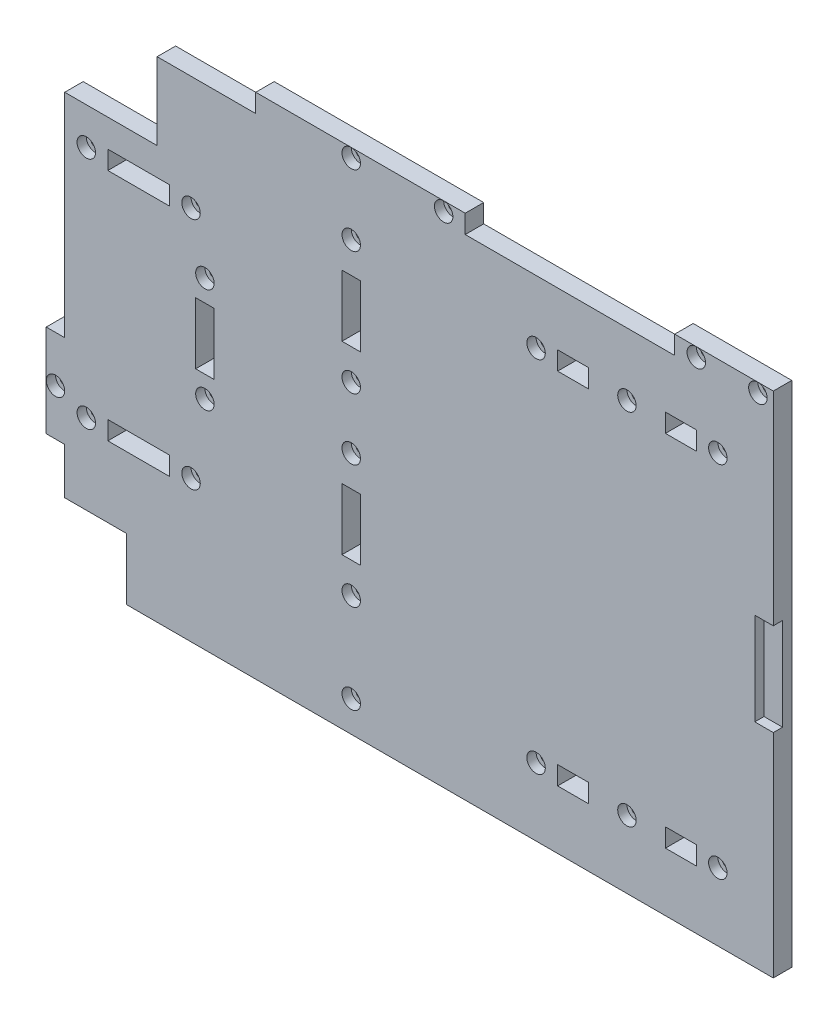
SolidWorks part; units mm, degrees
ref_plane "Plan de face" through (0, 0, 0) normal (0, 0, 1) x (1, 0, 0)
ref_plane "Plan de dessus" through (0, 0, 0) normal (0, 1, 0) x (1, 0, 0)
ref_plane "Plan de droite" through (0, 0, 0) normal (1, 0, 0) x (0, 0, -1)
sketch "Esquisse1" plane through (0, 0, 0) normal (0, 0, 1) x (1, 0, 0)
  line L1 (0, 0) -> (-340, 0)
  line L2 (0, 0) -> (0, 148)
  line L3 (0, 148) -> (-340, 148)
  line L4 (-340, 0) -> (-340, 148)
  dimension "D1" = 148
  dimension "D2" = 340
extrude "Boss.-Extru.1" add sketch "Esquisse1" along normal blind 6
sketch "Esquisse2" plane through (0, 0, 6) normal (0, 0, 1) x (1, 0, 0)
  line L0 (0, 0) -> (0, 148) construction
  line L1 (0, 148) -> (-340, 148) construction
  line L2 (-272, 142) -> (-334, 142)
  line L3 (-340, 148) -> (-340, 48)
  line L4 (0, 148) -> (0, 118)
  line L5 (0, 0) -> (-6, 0)
  line L6 (-340, 148) -> (-272, 148)
  line L7 (0, 0) -> (0, 28)
  line L8 (-340, 48) -> (-334, 48)
  line L9 (-334, 142) -> (-334, 48)
  line L11 (-340, 0) -> (-334, 0)
  line L12 (-340, 0) -> (-340, 18)
  line L13 (0, 28) -> (-6, 28)
  line L14 (-272, 148) -> (-272, 142)
  line L15 (-204, 148) -> (-136, 148)
  line L16 (-204, 148) -> (-204, 142)
  line L17 (-204, 142) -> (-136, 142)
  line L18 (-6, 0) -> (-6, 28)
  line L19 (0, 58) -> (-6, 58)
  line L20 (0, 58) -> (0, 88)
  line L21 (0, 88) -> (-6, 88)
  line L22 (-136, 148) -> (-136, 142)
  line L23 (0, 148) -> (-68, 148)
  line L24 (-340, 18) -> (-334, 18)
  line L25 (-6, 142) -> (-68, 142)
  line L26 (-68, 148) -> (-68, 142)
  line L27 (-334, 0) -> (-334, 18)
  line L29 (-6, 58) -> (-6, 88)
  line L32 (0, 118) -> (-6, 118)
  line L33 (-6, 142) -> (-6, 118)
  dimension "D3" = 68
  dimension "D4" = 6
  dimension "D5" = 100
  dimension "D6" = 68
  dimension "D7" = 30
  dimension "D8" = 6
  dimension "D9" = 30
  dimension "D10" = 30
  dimension "D11" = 24
  dimension "D12" = 30
  dimension "D13" = 6
  dimension "D14" = 68
  dimension "D15" = 6
  dimension "D16" = 6
  dimension "D18" = 6
  dimension "D20" = 6
  dimension "D21" = 6
extrude "Enlèv. mat.-Extru.1" cut sketch "Esquisse2" against normal blind 6
sketch "Esquisse3" plane through (0, 0, 6) normal (0, 0, 1) x (1, 0, 0)
  line L0 (-204, 148) -> (-272, 148) construction
  line L1 (-238, 32) -> (-244, 32)
  line L2 (-340, 48) -> (-340, 18) construction
  line L3 (-238, 112) -> (-244, 112)
  line L4 (-238, 112) -> (-238, 92)
  line L5 (-238, 92) -> (-244, 92)
  line L6 (-340, 48) -> (-340, 18) construction
  line L7 (-238, 52) -> (-244, 52)
  line L8 (-238, 52) -> (-238, 32)
  line L9 (-244, 112) -> (-244, 92)
  line L10 (-244, 52) -> (-244, 32)
  line L11 (-285.5, 80.5) -> (-291.5, 80.5)
  line L12 (-334, 0) -> (-6, 0) construction
  line L13 (-285.5, 80.5) -> (-285.5, 60.5)
  line L14 (-285.5, 60.5) -> (-291.5, 60.5)
  line L15 (-291.5, 80.5) -> (-291.5, 60.5)
  line L16 (-68, 142) -> (-6, 142) construction
  line L17 (-334, 142) -> (-304, 142)
  line L18 (-334, 142) -> (-334, 117)
  line L19 (-334, 117) -> (-304, 117)
  line L20 (-304, 142) -> (-304, 117)
  line L21 (-300, 108) -> (-320, 108)
  line L22 (-300, 108) -> (-300, 102)
  line L23 (-300, 102) -> (-320, 102)
  line L24 (-320, 108) -> (-320, 102)
  line L25 (-300, 32) -> (-320, 32)
  line L26 (-300, 32) -> (-300, 26)
  line L27 (-300, 26) -> (-320, 26)
  line L28 (-320, 32) -> (-320, 26)
  line L29 (-64, 112) -> (-70, 112)
  line L30 (-64, 112) -> (-64, 92)
  line L31 (-64, 92) -> (-70, 92)
  line L32 (-70, 112) -> (-70, 92)
  line L33 (0, 88) -> (0, 118) construction
  dimension "D1" = 20
  dimension "D2" = 20
  dimension "D3" = 40
  dimension "D4" = 96
  dimension "D5" = 96
  dimension "D6" = 6
  dimension "D7" = 6
  dimension "D8" = 92
  dimension "D9" = 6
  dimension "D10" = 20
  dimension "D11" = 48.5
  dimension "D12" = 67.5
  dimension "D13" = 30
  dimension "D14" = 25
  dimension "D15" = 20
  dimension "D16" = 6
  dimension "D17" = 40
  dimension "D18" = 20
  dimension "D19" = 20
  dimension "D20" = 6
  dimension "D21" = 70
  dimension "D22" = 20
  dimension "D23" = 20
  dimension "D24" = 30
  dimension "D25" = 6
  dimension "D26" = 70
extrude "Enlèv. mat.-Extru.2" cut sketch "Esquisse3" against normal blind 10
sketch "Esquisse4" plane through (0, 0, 6) normal (0, 0, 1) x (1, 0, 0)
  line L0 (-334, 48) -> (-334, 117) construction
  line L1 (-164, 124.6) -> (-174, 124.6)
  line L2 (-164, 124.6) -> (-164, 118.6)
  line L3 (-164, 118.6) -> (-174, 118.6)
  line L4 (-174, 124.6) -> (-174, 118.6)
  line L5 (-204, 148) -> (-272, 148) construction
  line L6 (-68, 148) -> (-136, 148) construction
  line L7 (-139, 124.6) -> (-129, 124.6)
  line L8 (-139, 124.6) -> (-139, 118.6)
  line L9 (-139, 118.6) -> (-129, 118.6)
  line L10 (-129, 124.6) -> (-129, 118.6)
  line L12 (-129, 8) -> (-139, 8)
  line L13 (-129, 8) -> (-129, 2)
  line L14 (-129, 2) -> (-139, 2)
  line L15 (-139, 8) -> (-139, 2)
  line L16 (-68, 148) -> (-136, 148) construction
  line L17 (-164, 8) -> (-174, 8)
  line L18 (-164, 8) -> (-164, 2)
  line L19 (-164, 2) -> (-174, 2)
  line L20 (-174, 8) -> (-174, 2)
  line L21 (-204, 148) -> (-272, 148) construction
  line L22 (-204, 142) -> (-136, 142) construction
  line L23 (-340, 48) -> (-340, 18) construction
  circle A0 centre (-151.5, 121.6) radius 1.5
  circle A1 centre (-151.5, 5) radius 1.5
  dimension "D7" = 3
  dimension "D14" = 140
  dimension "D16" = 137
  dimension "D19" = 3
  dimension "D1" = 10
  dimension "D2" = 6
  dimension "D3" = 160
  dimension "D4" = 23.4
  dimension "D5" = 10
  dimension "D6" = 25
  dimension "D8" = 12.5
  dimension "D9" = 23.4
  dimension "D10" = 26.4
  dimension "D11" = 6
  dimension "D12" = 6
  dimension "D13" = 6
  dimension "D15" = 140
  dimension "D17" = 12.5
  dimension "D18" = 25
  dimension "D20" = 166
  dimension "D21" = 10
  dimension "D22" = 10
extrude "Enlèv. mat.-Extru.3" cut sketch "Esquisse4" against normal blind 10
sketch "Esquisse7" plane through (0, 0, 0) normal (0, -1, 0) x (1, 0, 0)
  line L0 (-334, 6) -> (-6, 6) construction
  line L1 (-334, 6) -> (-6, 6)
  line L2 (-334, 6) -> (-334, 0)
  line L3 (-334, 0) -> (-6, 0)
  line L4 (-6, 6) -> (-6, 0)
  line L5 (-340, 6) -> (-340, 0) construction
  dimension "D1" = 6
extrude "Boss.-Extru.2" add sketch "Esquisse7" along normal blind 17
sketch "Esquisse8" plane through (0, 0, 6) normal (0, 0, 1) x (1, 0, 0)
  line L0 (-241, 115.6483) -> (-241, 35.6483) construction
  line L1 (-334, -17) -> (-314, -17)
  line L2 (-334, -17) -> (-334, 3)
  line L3 (-334, 3) -> (-314, 3)
  line L4 (-314, -17) -> (-314, 3)
  line L5 (-174, 124.6) -> (-174, 118.6) construction
  line L6 (-164, 124.6) -> (-174, 124.6) construction
  line L7 (-300, 102) -> (-300, 108) construction
  line L8 (-300, 108) -> (-320, 108) construction
  line L9 (-285.5, 80.5) -> (-291.5, 80.5) construction
  line L10 (-285.5, 60.5) -> (-285.5, 80.5) construction
  line L11 (-291.5, 60.5) -> (-285.5, 60.5) construction
  line L12 (-291.5, 80.5) -> (-291.5, 60.5) construction
  line L13 (-320, 108) -> (-320, 102) construction
  line L14 (-300, 26) -> (-300, 32) construction
  line L15 (-300, 32) -> (-320, 32) construction
  line L16 (-320, 32) -> (-320, 26) construction
  line L17 (-340, 48) -> (-340, 18) construction
  line L18 (-334, 18) -> (-340, 18) construction
  line L19 (-204, 148) -> (-272, 148) construction
  line L20 (-238, 112) -> (-244, 112) construction
  line L21 (-244, 92) -> (-238, 92) construction
  line L22 (-238, 52) -> (-244, 52) construction
  line L23 (-244, 32) -> (-238, 32) construction
  line L24 (-6, -17) -> (-334, -17) construction
  line L25 (-334, 48) -> (-334, 117) construction
  line L26 (-204, 148) -> (-204, 142) construction
  line L27 (-68, 148) -> (-136, 148) construction
  line L28 (-136, 142) -> (-136, 148) construction
  line L29 (-68, 148) -> (-68, 142) construction
  line L30 (-129, 118.6) -> (-129, 124.6) construction
  line L31 (-139, 118.6) -> (-129, 118.6) construction
  line L32 (-174, 8) -> (-174, 2) construction
  line L33 (-174, 2) -> (-164, 2) construction
  line L34 (-129, 2) -> (-129, 8) construction
  line L36 (-129, 8) -> (-139, 8) construction
  line L37 (0, 88) -> (-6, 88) construction
  line L39 (-6, 88) -> (-6, 58) construction
  line L40 (0, 88) -> (0, 118) construction
  line L41 (-6, 118) -> (0, 118) construction
  line L42 (0, 28) -> (0, 58) construction
  line L43 (-6, 58) -> (0, 58) construction
  line L45 (0, 28) -> (-6, 28) construction
  circle A0 centre (-75, 145) radius 1.5
  circle A1 centre (-129, 145) radius 1.5
  circle A2 centre (-109, 145) radius 1.5
  circle A3 centre (-3, 111) radius 1.5
  circle A4 centre (-3, 95) radius 1.5
  circle A5 centre (-3, 51) radius 1.5
  circle A6 centre (-3, 35) radius 1.5
  circle A7 centre (-122, 121.6) radius 1.5
  circle A8 centre (-181, 121.6) radius 1.5
  circle A9 centre (-122, 5) radius 1.5
  circle A10 centre (-181, 5) radius 1.5
  circle A11 centre (-211, 145) radius 1.5
  circle A12 centre (-241, 145) radius 1.5
  circle A13 centre (-241, 122) radius 1.5
  circle A14 centre (-241, 82) radius 1.5
  circle A15 centre (-241, 62) radius 1.5
  circle A16 centre (-241, 22) radius 1.5
  circle A17 centre (-241, -7) radius 1.5
  circle A18 centre (-288.5, 87.5) radius 1.5
  circle A19 centre (-288.5, 53.5) radius 1.5
  circle A20 centre (-293, 105) radius 1.5
  circle A21 centre (-327, 105) radius 1.5
  circle A22 centre (-293, 29) radius 1.5
  circle A23 centre (-327, 29) radius 1.5
  circle A24 centre (-337, 33) radius 1.5
  point P105 (-68, 145)
  point P118 (-3, 28)
  dimension "D3" = 3
  dimension "D4" = 3
  dimension "D5" = 3
  dimension "D6" = 3
  dimension "D7" = 3
  dimension "D8" = 3
  dimension "D9" = 3
  dimension "D10" = 7
  dimension "D11" = 3
  dimension "D12" = 7
  dimension "D13" = 3
  dimension "D14" = 7
  dimension "D15" = 3
  dimension "D16" = 7
  dimension "D17" = 3
  dimension "D18" = 7
  dimension "D19" = 3
  dimension "D20" = 7
  dimension "D21" = 3
  dimension "D22" = 3
  dimension "D23" = 15
  dimension "D24" = 3
  dimension "D25" = 3
  dimension "D26" = 3
  dimension "D27" = 10
  dimension "D28" = 3
  dimension "D29" = 10
  dimension "D30" = 3
  dimension "D31" = 10
  dimension "D32" = 3
  dimension "D33" = 10
  dimension "D34" = 3
  dimension "D35" = 10
  dimension "D37" = 3
  dimension "D38" = 7
  dimension "D39" = 3
  dimension "D40" = 3
  dimension "D41" = 7
  dimension "D42" = 3
  dimension "D43" = 3
  dimension "D44" = 3
  dimension "D45" = 7
  dimension "D46" = 3
  dimension "D47" = 3
  dimension "D48" = 3
  dimension "D50" = 7
  dimension "D52" = 3
  dimension "D53" = 7
  dimension "D54" = 3
  dimension "D55" = 3
  dimension "D56" = 7
  dimension "D57" = 3
  dimension "D58" = 7
  dimension "D59" = 3
  dimension "D60" = 3
  dimension "D61" = 3
  dimension "D62" = 7
  dimension "D63" = 3
  dimension "D64" = 3
  dimension "D65" = 3
  dimension "D66" = 7
  dimension "D67" = 3
  dimension "D68" = 3
  dimension "D69" = 7
  dimension "D70" = 3
  dimension "D71" = 7
  dimension "D72" = 3
  dimension "D51" = 20
  dimension "D1" = 20
  dimension "D2" = 20
  dimension "D36" = 93
  dimension "D49" = 3
extrude "Enlèv. mat.-Extru.5" cut sketch "Esquisse8" against normal through all
sketch "Esquisse9" plane through (0, 0, 6) normal (0, 0, 1) x (1, 0, 0)
  circle A0 centre (-337, 33) radius 2.995
  circle A1 centre (-327, 29) radius 3
  circle A2 centre (-293, 29) radius 3
  circle A3 centre (-288.5, 53.5) radius 3
  circle A4 centre (-288.5, 87.5) radius 3
  circle A5 centre (-293, 105) radius 3
  circle A6 centre (-327, 105) radius 3
  circle A7 centre (-241, 145) radius 2.995
  circle A8 centre (-241, 122) radius 2.995
  circle A9 centre (-241, 82) radius 2.995
  circle A10 centre (-241, 62) radius 3
  circle A11 centre (-241, 22) radius 3
  circle A12 centre (-241, -7) radius 3
  circle A13 centre (-211, 145) radius 2.995
  circle A15 centre (-181, 121.6) radius 2.995
  circle A16 centre (-151.5, 121.6) radius 2.995
  circle A17 centre (-129, 145) radius 2.995
  circle A19 centre (-122, 121.6) radius 2.995
  circle A21 centre (-109, 145) radius 2.995
  circle A23 centre (-122, 5) radius 2.995
  circle A24 centre (-151.5, 5) radius 2.995
  circle A25 centre (-181, 5) radius 2.995
  circle A26 centre (-75, 145) radius 2.995
  circle A27 centre (-3, 111) radius 2.995
  circle A28 centre (-3, 95) radius 2.995
  circle A29 centre (-3, 51) radius 2.995
  circle A30 centre (-3, 35) radius 2.995
  dimension "D1" = 5.99
  dimension "D2" = 5.99
  dimension "D3" = 5.99
  dimension "D4" = 5.99
  dimension "D5" = 5.99
  dimension "D6" = 5.99
  dimension "D7" = 5.99
  dimension "D8" = 5.99
  dimension "D9" = 5.99
  dimension "D10" = 5.99
  dimension "D11" = 5.99
  dimension "D12" = 5.99
  dimension "D13" = 5.99
  dimension "D14" = 5.99
  dimension "D15" = 6
  dimension "D16" = 6
  dimension "D17" = 6
  dimension "D18" = 5.99
  dimension "D19" = 5.99
  dimension "D20" = 5.99
  dimension "D21" = 6
  dimension "D22" = 6
  dimension "D23" = 6
  dimension "D24" = 6
  dimension "D25" = 6
  dimension "D26" = 6
  dimension "D27" = 5.99
extrude "Enlèv. mat.-Extru.8" cut sketch "Esquisse9" against normal blind 3
sketch "Esquisse10" plane through (0, 0, 6) normal (0, 0, 1) x (1, 0, 0)
  line L1 (-68, 148) -> (-136, 148) construction
  line L2 (26.302, -46.0773) -> (-104, -46.0773)
  line L3 (26.302, -46.0773) -> (26.302, 148)
  line L4 (26.302, 148) -> (-104, 148)
  line L6 (-104, 148) -> (-104, -46.0773)
extrude "Enlèv. mat.-Extru.9" cut sketch "Esquisse10" against normal through all
sketch "Esquisse11" plane through (0, 0, 6) normal (0, 0, 1) x (1, 0, 0)
  line L0 (-104, 148) -> (-104, -17) construction
  line L1 (-104, 82) -> (-110, 82)
  line L2 (-104, 82) -> (-104, 52)
  line L3 (-104, 52) -> (-110, 52)
  line L4 (-110, 82) -> (-110, 52)
  line L5 (-104, 148) -> (-136, 148) construction
  dimension "D1" = 6
  dimension "D2" = 30
  dimension "D3" = 66
extrude "Enlèv. mat.-Extru.10" cut sketch "Esquisse11" against normal blind 3
